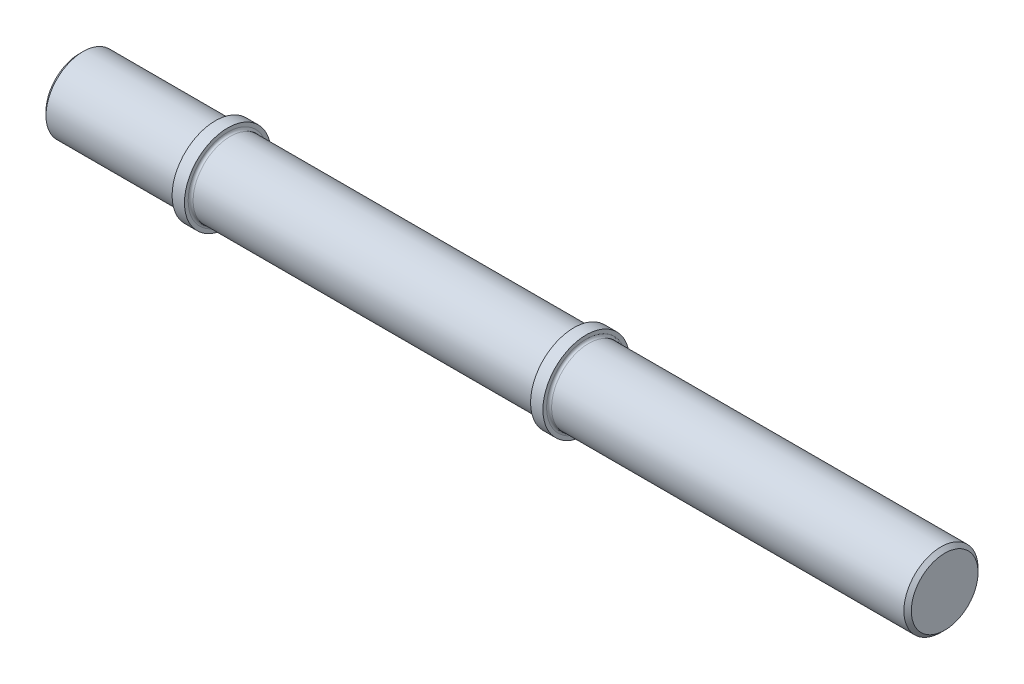
SolidWorks part; units mm, degrees
ref_plane "Front Plane" through (0, 0, 0) normal (0, 0, 1) x (1, 0, 0)
ref_plane "Top Plane" through (0, 0, 0) normal (0, 1, 0) x (1, 0, 0)
ref_plane "Right Plane" through (0, 0, 0) normal (1, 0, 0) x (0, 0, -1)
sketch "Sketch1" plane through (0, 0, 0) normal (0, 0, 1) x (1, 0, 0)
  line L0 (0, 0) -> (175.6987, 0) construction
  line L1 (12, 3) -> (12, 3.5)
  line L2 (0, 0) -> (70, 0)
  line L3 (0, 0) -> (0, 3)
  line L4 (0, 3) -> (11, 3)
  line L5 (70, 0) -> (70, 3)
  line L6 (12, 3.5) -> (11, 3.5)
  line L7 (11, 3.5) -> (11, 3)
  line L8 (40, 3) -> (40, 3.5)
  line L9 (40, 3.5) -> (41, 3.5)
  line L10 (41, 3.5) -> (41, 3)
  line L11 (41, 3) -> (70, 3)
  line L12 (12, 3) -> (40, 3)
  line L15 (20, 3) -> (20, 0)
  line L16 (38, 3) -> (38, 0)
  line L17 (40, 3) -> (40, 0)
  line L18 (48, 3) -> (48, 0)
  line L19 (58, 3) -> (58, 0)
  dimension "D1" = 70
  dimension "D2" = 6
  dimension "D3" = 7
  dimension "D4" = 1
  dimension "D5" = 7
  dimension "D7" = 12
  dimension "D8" = 58
  dimension "D10" = 20
  dimension "D11" = 38
  dimension "D12" = 40
  dimension "D13" = 48
revolve "Revolve1" add sketch "Sketch1" angle 360 about L0
fillet "Fillet1" radius 0.2 4 edges at (11, 0, 3) (12, 0, 3) (40, 0, 3) (41, 0, 3)
chamfer "Chamfer1" distance 0.3 angle 45 2 edges at (70, 0, 3) (0, 0, 3)
